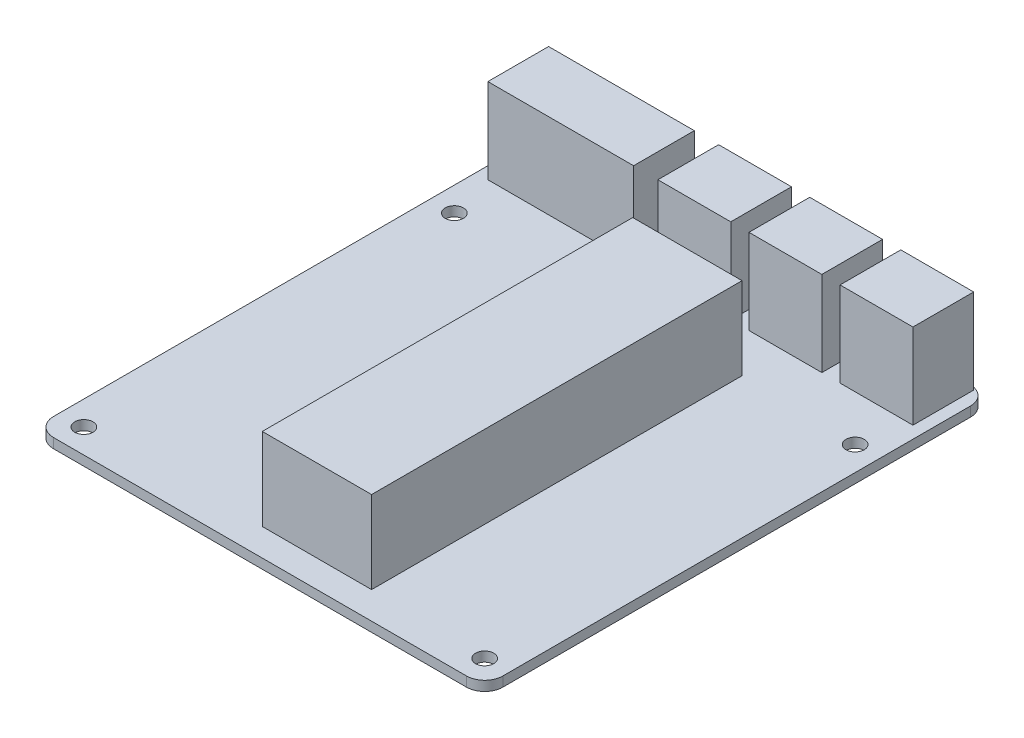
SolidWorks part; units mm, degrees
ref_plane "Front Plane" through (0, 0, 0) normal (0, 0, 1) x (1, 0, 0)
ref_plane "Top Plane" through (0, 0, 0) normal (0, 1, 0) x (1, 0, 0)
ref_plane "Right Plane" through (0, 0, 0) normal (1, 0, 0) x (0, 0, -1)
sketch "Sketch2" plane through (0, 0, 0) normal (0, 1, 0) x (1, 0, 0)
  line L1 (34, 41.5) -> (-34, 41.5)
  line L2 (37, 38.5) -> (37, -38.5)
  line L3 (34, -41.5) -> (-34, -41.5)
  line L4 (-37, 38.5) -> (-37, -38.5)
  line L5 (37, 41.5) -> (-37, -41.5) construction
  line L6 (37, -41.5) -> (-37, 41.5) construction
  arc A0 (-34, 41.5) -> (-37, 38.5) centre (-34, 38.5) ccw
  arc A1 (-34, -41.5) -> (-37, -38.5) centre (-34, -38.5) cw
  arc A2 (37, -38.5) -> (34, -41.5) centre (34, -38.5) cw
  arc A3 (34, 41.5) -> (37, 38.5) centre (34, 38.5) cw
  point P0 (0, 0)
  point P5 (0, 0)
  dimension "D3" = 3
  dimension "D1" = 83
  dimension "D2" = 74
extrude "Boss-Extrude1" add sketch "Sketch2" along normal blind 1.6
sketch "Sketch3" plane through (0, 1.6, 0) normal (0, 1, 0) x (1, 0, 0)
  line L0 (-37, 38.5) -> (-37, -38.5) construction
  line L1 (-34, -41.5) -> (34, -41.5) construction
  line L2 (37, -38.5) -> (37, 38.5) construction
  circle A0 centre (-33, 23.5) radius 1.5
  circle A1 centre (33, 23.5) radius 1.5
  circle A2 centre (-33, -37.5) radius 1.5
  circle A3 centre (33, -37.5) radius 1.5
  point P8 (0, 0)
  point P9 (0, 0)
  point P10 (0, 0)
  dimension "D3" = 3
  dimension "D1" = 4
  dimension "D2" = 4
  dimension "D4" = 4
  dimension "D5" = 65
extrude "Cut-Extrude1" cut sketch "Sketch3" against normal through all both and the other way through all
sketch "Sketch4" plane through (0, 1.6, 0) normal (0, 1, 0) x (1, 0, 0)
  line L0 (-37, 38.5) -> (-37, -38.5) construction
  line L1 (-11, 41.0224) -> (-35, 41.0224)
  line L2 (-11, 41.0224) -> (-11, 31.0224)
  line L3 (-11, 31.0224) -> (-35, 31.0224)
  line L4 (-35, 41.0224) -> (-35, 31.0224)
  line L5 (-11, 41.0224) -> (-35, 31.0224) construction
  line L6 (-11, 31.0224) -> (-35, 41.0224) construction
  line L7 (5, 41.0224) -> (-7, 41.0224)
  line L8 (5, 41.0224) -> (5, 31.0224)
  line L9 (5, 31.0224) -> (-7, 31.0224)
  line L10 (-7, 41.0224) -> (-7, 31.0224)
  line L11 (5, 41.0224) -> (-7, 31.0224) construction
  line L12 (5, 31.0224) -> (-7, 41.0224) construction
  line L13 (20, 41.0224) -> (8, 41.0224)
  line L14 (20, 41.0224) -> (20, 31.0224)
  line L15 (20, 31.0224) -> (8, 31.0224)
  line L16 (8, 41.0224) -> (8, 31.0224)
  line L17 (20, 41.0224) -> (8, 31.0224) construction
  line L18 (20, 31.0224) -> (8, 41.0224) construction
  line L19 (35, 41.0224) -> (23, 41.0224)
  line L20 (35, 41.0224) -> (35, 31.0224)
  line L21 (35, 31.0224) -> (23, 31.0224)
  line L22 (23, 41.0224) -> (23, 31.0224)
  line L23 (35, 41.0224) -> (23, 31.0224) construction
  line L24 (35, 31.0224) -> (23, 41.0224) construction
  line L25 (34, 41.5) -> (-34, 41.5) construction
  point P0 (-23, 36.0224)
  point P5 (-1, 36.0224)
  point P10 (14, 36.0224)
  point P15 (29, 36.0224)
  dimension "D1" = 14
  dimension "D2" = 36
  dimension "D3" = 51
  dimension "D4" = 66
  dimension "D5" = 5.4776
  dimension "D6" = 10
  dimension "D7" = 12
  dimension "D8" = 24
extrude "Boss-Extrude2" add sketch "Sketch4" along normal blind 14
sketch "Sketch5" plane through (0, 1.6, 0) normal (0, 1, 0) x (1, 0, 0)
  line L0 (-37, 38.5) -> (-37, -38.5) construction
  line L1 (13.88, 24) -> (-4.12, 24)
  line L2 (13.88, 24) -> (13.88, -37)
  line L3 (13.88, -37) -> (-4.12, -37)
  line L4 (-4.12, 24) -> (-4.12, -37)
  line L5 (13.88, 24) -> (-4.12, -37) construction
  line L6 (13.88, -37) -> (-4.12, 24) construction
  line L7 (-34, -41.5) -> (34, -41.5) construction
  point P0 (4.88, -6.5)
  dimension "D1" = 41.88
  dimension "D2" = 35
  dimension "D3" = 61
  dimension "D4" = 18
extrude "Boss-Extrude3" add sketch "Sketch5" along normal blind 13.56
